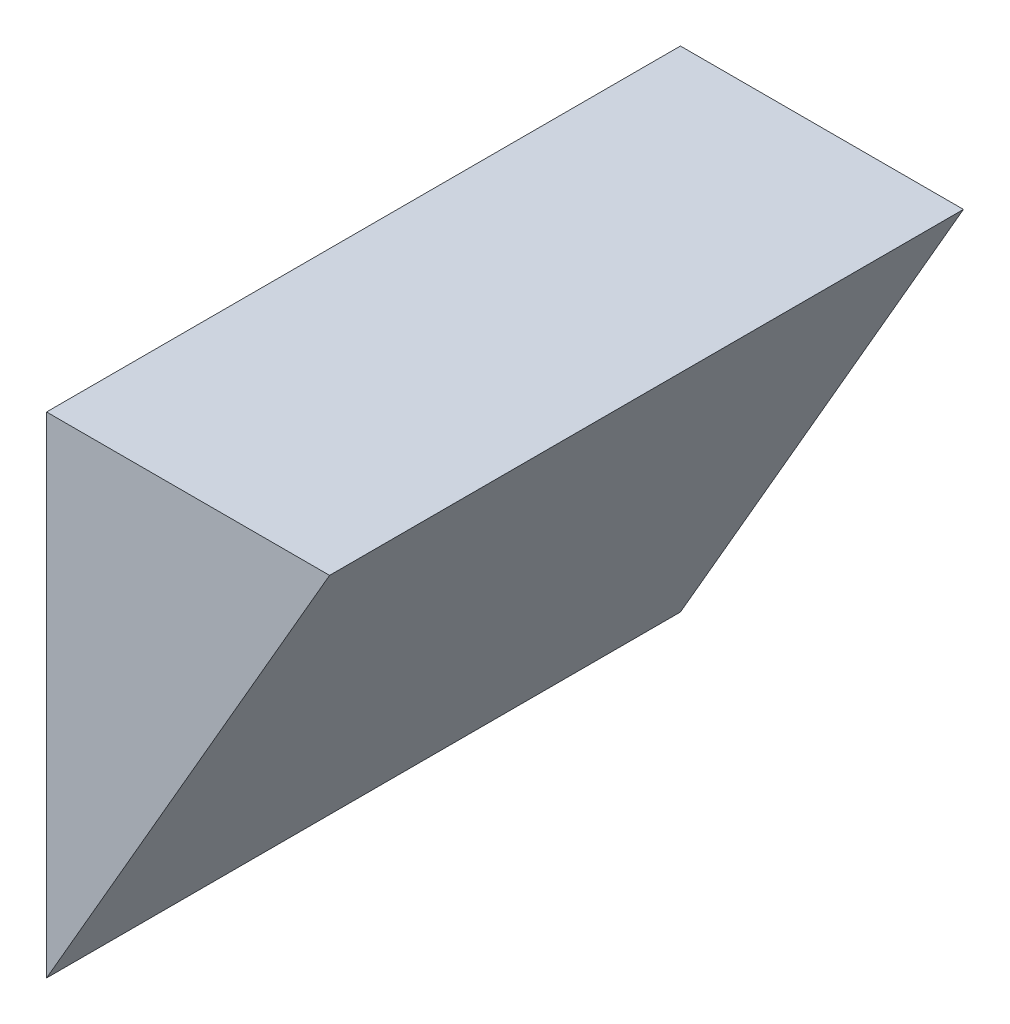
SolidWorks part; units mm, degrees
ref_plane "Front Plane" through (0, 0, 0) normal (0, 0, 1) x (1, 0, 0)
ref_plane "Top Plane" through (0, 0, 0) normal (0, 1, 0) x (1, 0, 0)
ref_plane "Right Plane" through (0, 0, 0) normal (1, 0, 0) x (0, 0, -1)
sketch "Sketch1" plane through (0, 0, 0) normal (0, 0, 1) x (1, 0, 0)
  line L0 (0, 0) -> (0, -15.4672)
  line L1 (0, -15.4672) -> (8.93, 0)
  line L2 (8.93, 0) -> (0, 0)
  dimension "D1" = 30
  dimension "D2" = 8.93
extrude "Boss-Extrude2" add sketch "Sketch1" along normal blind 20
